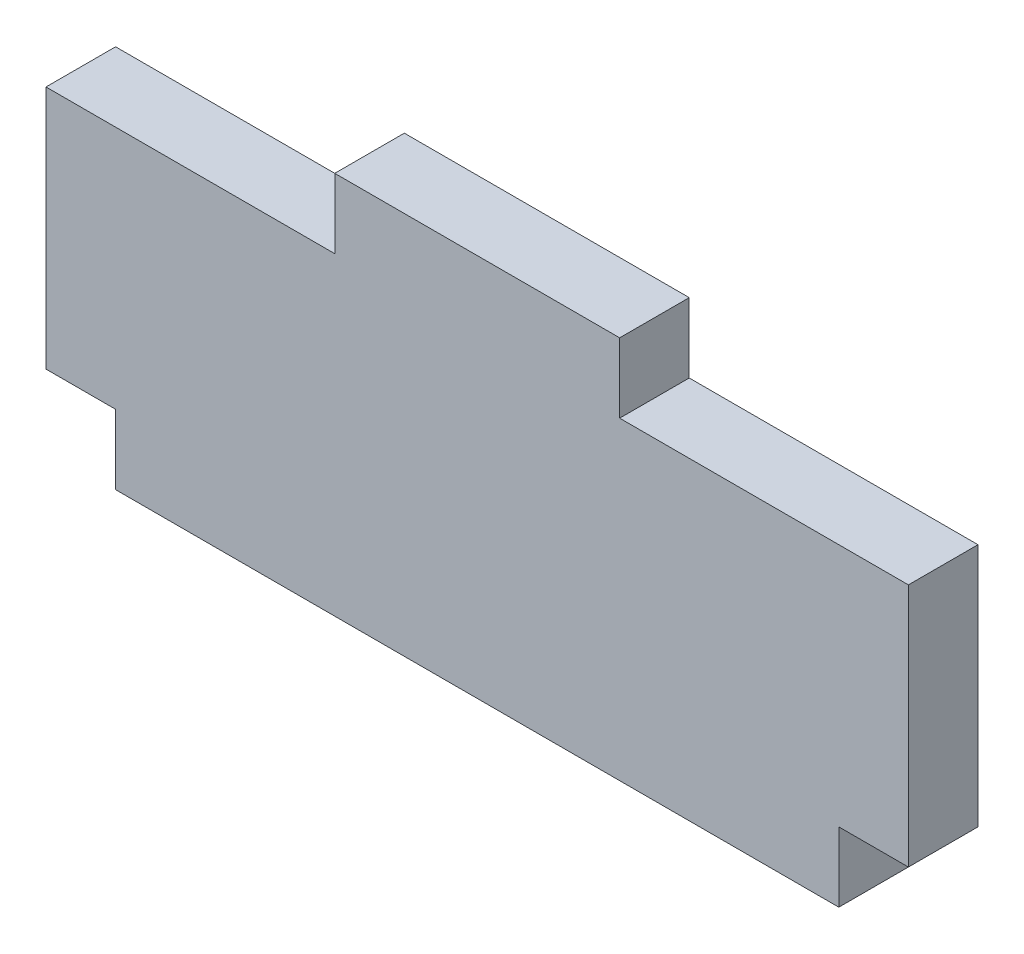
SolidWorks part; units mm, degrees
ref_plane "Front Plane" through (0, 0, 0) normal (0, 0, 1) x (1, 0, 0)
ref_plane "Top Plane" through (0, 0, 0) normal (0, 1, 0) x (1, 0, 0)
ref_plane "Right Plane" through (0, 0, 0) normal (1, 0, 0) x (0, 0, -1)
sketch "Sketch1" plane through (0, 0, 0) normal (0, 0, 1) x (1, 0, 0)
  line L0 (0, 0) -> (26.35, 0)
  line L1 (26.35, 0) -> (26.35, 6.35)
  line L2 (26.35, 6.35) -> (52.35, 6.35)
  line L3 (52.35, 6.35) -> (52.35, 0)
  line L4 (52.35, 0) -> (78.7, 0)
  line L8 (0, 0) -> (0, -22.3)
  line L9 (0, -22.3) -> (6.35, -22.3)
  line L10 (6.35, -22.3) -> (6.35, -28.65)
  line L11 (78.7, -22.3) -> (72.35, -22.3)
  line L12 (72.35, -22.3) -> (72.35, -28.65)
  line L13 (78.7, 0) -> (78.7, -22.3)
  line L14 (72.35, -28.65) -> (6.35, -28.65)
  dimension "D1" = 6.35
  dimension "D2" = 78.7
  dimension "D3" = 26
  dimension "D4" = 6.35
  dimension "D5" = 6.35
  dimension "D6" = 6.35
  dimension "D7" = 35
  dimension "D8" = 26.35
extrude "Boss-Extrude1" add sketch "Sketch1" along normal blind 6.35
